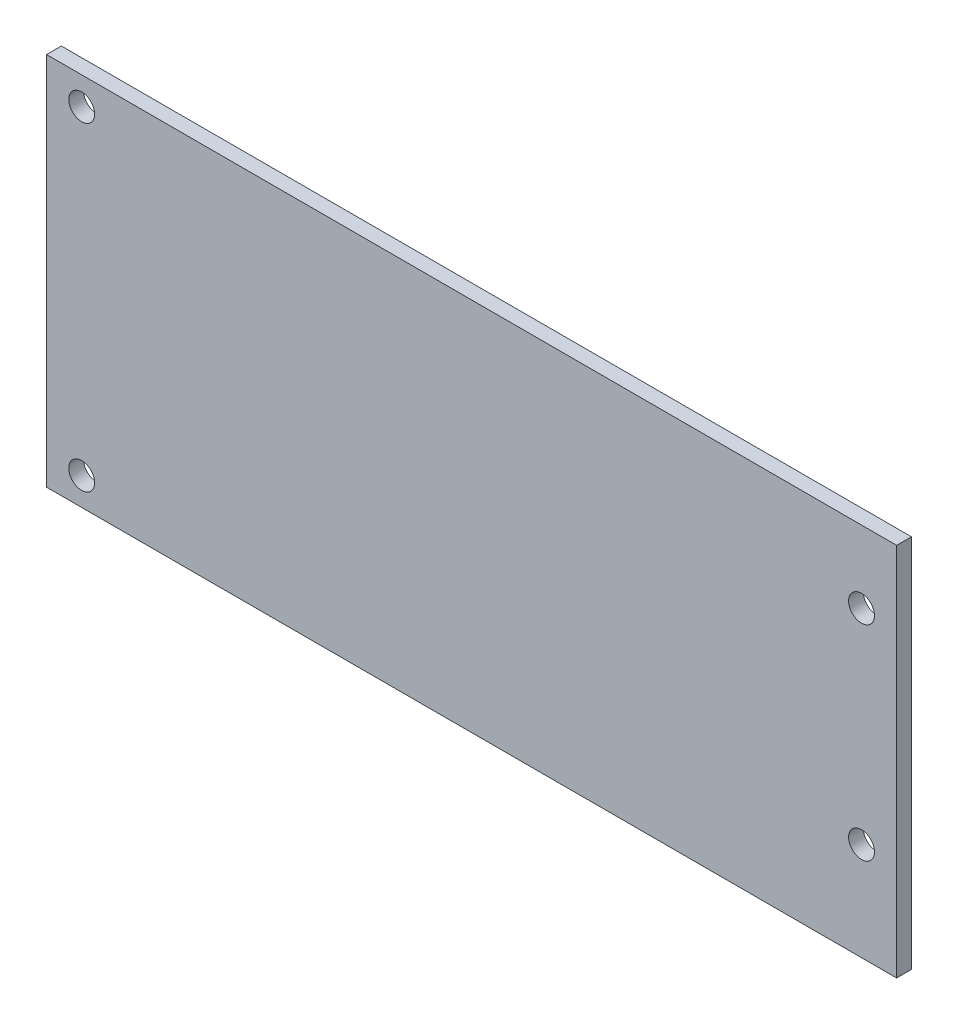
SolidWorks part; units mm, degrees
ref_plane "Front Plane" through (0, 0, 0) normal (0, 0, 1) x (1, 0, 0)
ref_plane "Top Plane" through (0, 0, 0) normal (0, 1, 0) x (1, 0, 0)
ref_plane "Right Plane" through (0, 0, 0) normal (1, 0, 0) x (0, 0, -1)
sketch "Sketch1" plane through (0, 0, 0) normal (0, 0, 1) x (1, 0, 0)
  line L1 (-56.3656, 34.3301) -> (58.6344, 34.3301)
  line L2 (-56.3656, 34.3301) -> (-56.3656, -16.3612)
  line L3 (-56.3656, -16.3612) -> (58.6344, -16.3612)
  line L4 (58.6344, 34.3301) -> (58.6344, -16.3612)
extrude "Boss-Extrude1" add sketch "Sketch1" along normal blind 2
sketch "Sketch2" plane through (0, 0, 2) normal (0, 0, 1) x (1, 0, 0)
  line L0 (-56.3656, 34.3301) -> (-51.6156, 34.3301)
  line L1 (58.6344, 34.3301) -> (-56.3656, 34.3301) construction
  line L2 (-51.6156, 34.3301) -> (-51.6156, 30.5801)
  line L3 (58.6344, 34.3301) -> (53.8844, 34.3301)
  line L4 (53.8844, 34.3301) -> (53.8844, 24.5801)
  line L5 (-56.3656, 8.9845) -> (58.6344, 8.9845)
  line L6 (-56.3656, 34.3301) -> (-56.3656, -16.3612) construction
  line L7 (58.6344, -16.3612) -> (58.6344, 34.3301) construction
  line L8 (53.8844, -16.3612) -> (53.8844, -3.1112)
  line L9 (-56.3656, -16.3612) -> (58.6344, -16.3612) construction
  line L10 (-56.3656, 34.3301) -> (-56.3656, 8.9845)
  line L11 (-56.3656, 8.9845) -> (-56.3656, -16.3612)
  line L12 (-56.3656, -16.3612) -> (53.8844, -16.3612)
  line L13 (58.6344, 8.9845) -> (58.6344, -16.3612)
  line L14 (58.6344, -16.3612) -> (53.8844, -16.3612)
  line L15 (1.1344, 8.9845) -> (1.1344, 34.3301)
  circle A0 centre (-51.6156, 30.5801) radius 1.75
  circle A1 centre (53.8844, 24.5801) radius 1.75
  circle A2 centre (-51.6156, -12.6112) radius 1.75
  circle A3 centre (53.8844, -3.1112) radius 1.75
extrude "Cut-Extrude1" cut sketch "Sketch2" against normal through all
